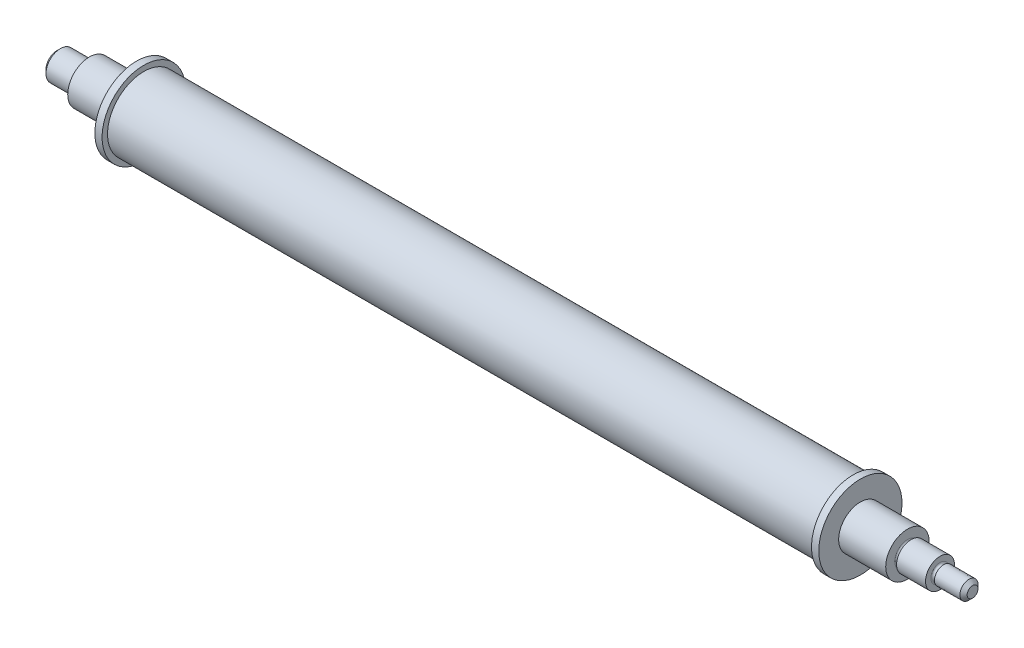
SolidWorks part; units mm, degrees
ref_plane "Front Plane" through (0, 0, 0) normal (0, 0, 1) x (1, 0, 0)
ref_plane "Top Plane" through (0, 0, 0) normal (0, 1, 0) x (1, 0, 0)
ref_plane "Right Plane" through (0, 0, 0) normal (1, 0, 0) x (0, 0, -1)
sketch "Sketch2" plane through (0, 0, 0) normal (1, 0, 0) x (0, 0, -1)
  circle A0 centre (0, 0) radius 10
  dimension "D1" = 20
extrude "Boss-Extrude1" add sketch "Sketch2" along normal blind 98
sketch "Sketch11" plane through (98, 0, 0) normal (1, 0, 0) x (0, 0, -1)
  circle A0 centre (0, 0) radius 11.5
  dimension "D1" = 23
extrude "Boss-Extrude3" add sketch "Sketch11" along normal blind 2
sketch "Sketch13" plane through (100, 0, 0) normal (1, 0, 0) x (0, 0, -1)
  circle A0 centre (0, 0) radius 7.5
  dimension "D1" = 15
mirror "Mirror3" about plane through (0, 0, 0) normal (1, 0, 0) of bodies 112 116
sketch "Sketch14" plane through (0, 0, 0) normal (0, 0, 1) x (1, 0, 0)
  line L0 (0, 0) -> (188.4387, 0) construction
  line L1 (100, 0) -> (100, 6)
  line L2 (100, -7.5) -> (100, 7.5) construction
  line L3 (100, 6) -> (113, 6)
  line L4 (113, 6) -> (113, 3.5)
  line L5 (114.5, 4) -> (114, 4)
  line L6 (114, 4) -> (114, 3.5)
  line L7 (114.5, 4) -> (122, 4)
  line L8 (122, 4) -> (122, 3)
  line L12 (122, 2.5235) -> (122, 3)
  line L13 (131, 0) -> (131, 2.5)
  line L14 (131, 2.5) -> (123, 2.5235)
  line L15 (100, 0) -> (131, 0)
  arc A0 (122.5, 2.0235) -> (123, 2.5235) centre (122.5, 2.5235) ccw
  arc A1 (113, 3.5) -> (113.5, 3) centre (113.5, 3.5) ccw
  arc A3 (113, 3.5) -> (114, 3.5) centre (113.5, 3.5) ccw
  arc A4 (122, 2.5235) -> (123, 2.5235) centre (122.5, 2.5235) ccw
  point P21 (120.8462, 3)
  point P24 (114, 4)
  dimension "D6" = 0.5
  dimension "D7" = 0.5
  dimension "D1" = 6
  dimension "D2" = 3
  dimension "D4" = 13
  dimension "D5" = 8
revolve "Revolve1" add sketch "Sketch14" angle 360 about L0
chamfer "Chamfer2" distance 1 angle 45 1 edges at (131, 0, 2.5)
mirror "Mirror6" about plane through (0, 0, 0) normal (1, 0, 0) of "Revolve1"
sketch "Sketch15" plane through (-131, 0, 0) normal (-1, 0, 0) x (0, 0, 1)
  circle A0 centre (0, 0) radius 2.5235
extrude "Cut-Extrude2" cut sketch "Sketch15" against normal blind 9
chamfer "Chamfer4" distance 1 angle 45 1 edges at (-122, 0, 4)
